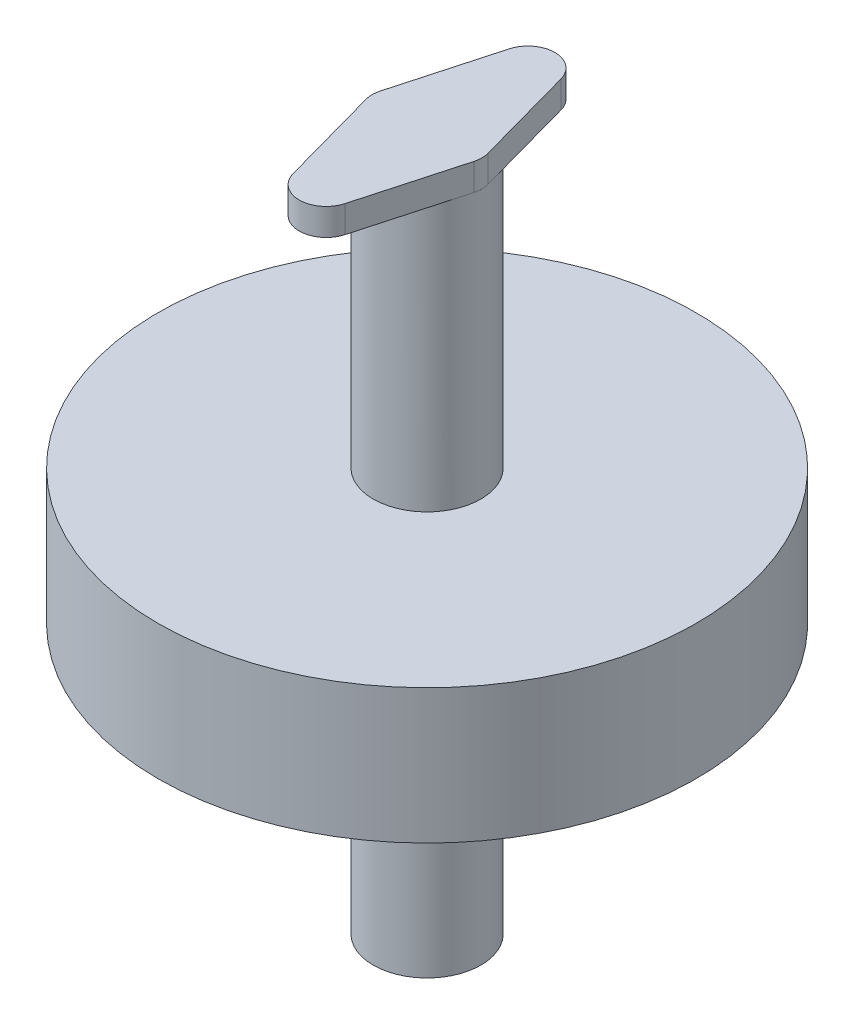
SolidWorks part; units mm, degrees
ref_plane "Alzado" through (0, 0, 0) normal (0, 0, 1) x (1, 0, 0)
ref_plane "Planta" through (0, 0, 0) normal (0, 1, 0) x (1, 0, 0)
ref_plane "Vista lateral" through (0, 0, 0) normal (1, 0, 0) x (0, 0, -1)
sketch "Croquis1" plane through (0, 0, 0) normal (0, 1, 0) x (1, 0, 0)
  circle A0 centre (0, 0) radius 10
  dimension "D1" = 20
extrude "Saliente-Extruir1" add sketch "Croquis1" along normal blind 5
sketch "Croquis2" plane through (0, 5, 0) normal (0, 1, 0) x (1, 0, 0)
  circle A0 centre (0, 0) radius 2
  dimension "D1" = 4
extrude "Saliente-Extruir2" add sketch "Croquis2" along normal blind 10 and the other way blind 15
sketch "Croquis3" plane through (0, 15, 0) normal (0, 1, 0) x (1, 0, 0)
  line L0 (-2.0751, 0) -> (0, 7.5)
  line L1 (0, 7.5) -> (2.0751, 0)
  line L2 (2.0751, 0) -> (0, -7.5)
  line L3 (0, -7.5) -> (-2.0751, 0)
  line L4 (0, 7.5) -> (0, -7.5) construction
  line L5 (-2.0751, 0) -> (2.0751, 0) construction
  circle A0 centre (0, 0) radius 2 construction
  dimension "D1" = 15
extrude "Saliente-Extruir3" add sketch "Croquis3" along normal blind 1
fillet "Redondeo1" radius 1 4 edges at (2.0751, 15.5, 0) (0, 15.5, 7.5) (-2.0751, 15.5, 0) (0, 15.5, -7.5)
